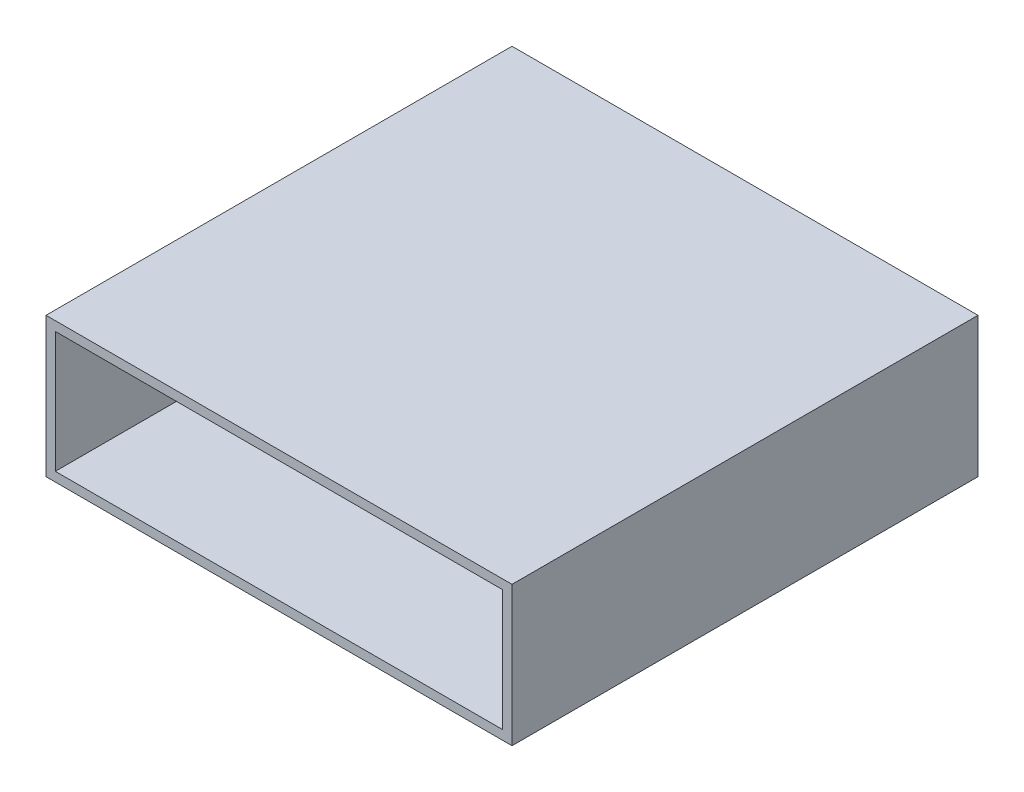
SolidWorks part; units mm, degrees
ref_plane "前视基准面" through (0, 0, 0) normal (0, 0, 1) x (1, 0, 0)
ref_plane "上视基准面" through (0, 0, 0) normal (0, 1, 0) x (1, 0, 0)
ref_plane "右视基准面" through (0, 0, 0) normal (1, 0, 0) x (0, 0, -1)
other "Configuration Table"
sketch "草图1" plane through (0, 0, 0) normal (0, 0, 1) x (1, 0, 0)
  line L1 (0, 0) -> (50, 0)
  line L2 (0, 0) -> (0, 15)
  line L3 (0, 15) -> (50, 15)
  line L4 (50, 0) -> (50, 15)
  line L5 (1, 1) -> (49, 1)
  line L6 (1, 1) -> (1, 14)
  line L7 (1, 14) -> (49, 14)
  line L8 (49, 1) -> (49, 14)
  dimension "D1" = 50
  dimension "D2" = 15
  dimension "D3" = 1
  dimension "D4" = 1
  dimension "D5" = 1
  dimension "D6" = 1
extrude "凸台-拉伸1" add sketch "草图1" along normal blind 50
